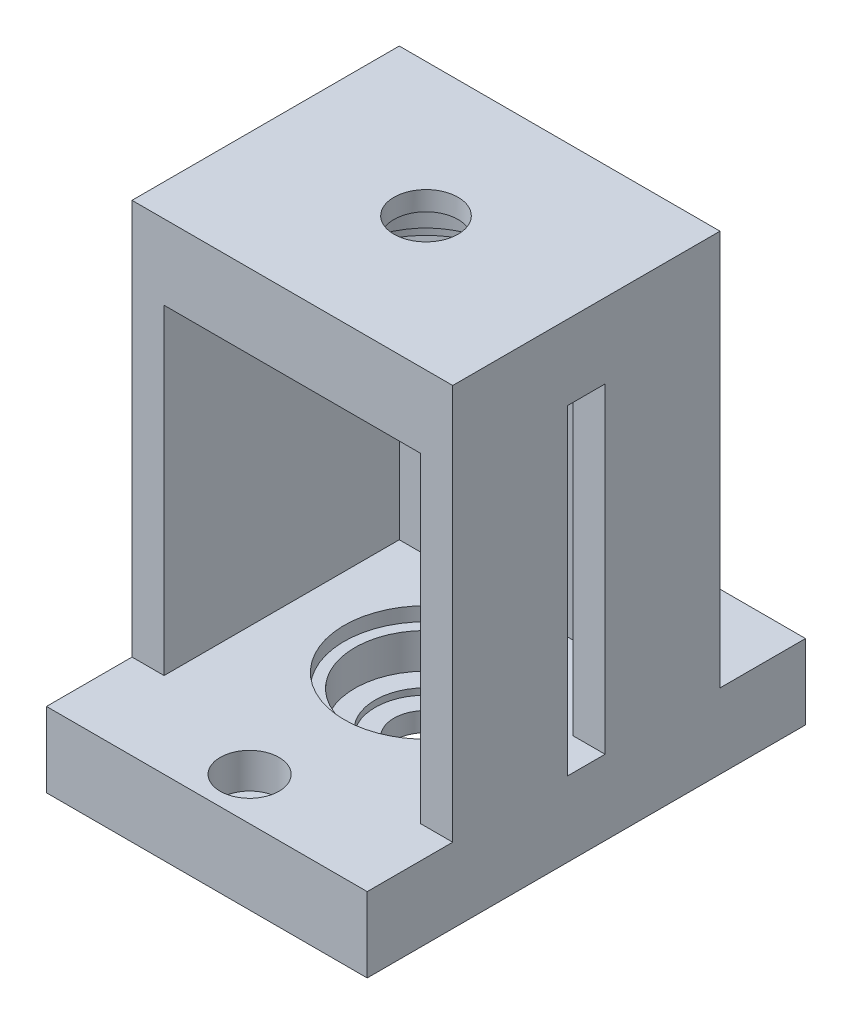
SolidWorks part; units mm, degrees
ref_plane "Front Plane" through (0, 0, 0) normal (0, 0, 1) x (1, 0, 0)
ref_plane "Top Plane" through (0, 0, 0) normal (0, 1, 0) x (1, 0, 0)
ref_plane "Right Plane" through (0, 0, 0) normal (1, 0, 0) x (0, 0, -1)
sketch "Sketch1" plane through (0, 0, 0) normal (0, 1, 0) x (1, 0, 0)
  line L1 (-15, -12.5) -> (15, -12.5)
  line L2 (-15, -12.5) -> (-15, 12.5)
  line L3 (-15, 12.5) -> (15, 12.5)
  line L4 (15, -12.5) -> (15, 12.5)
  line L5 (-15, -12.5) -> (15, 12.5) construction
  line L6 (-15, 12.5) -> (15, -12.5) construction
  point P0 (0, 0)
  dimension "D1" = 30
  dimension "D2" = 25
extrude "Boss-Extrude1" add sketch "Sketch1" along normal blind 7
sketch "Sketch2" plane through (0, 7, 0) normal (0, 1, 0) x (1, 0, 0)
  line L0 (-15, -12.5) -> (-12, -12.5)
  line L1 (-15, -12.5) -> (15, -12.5) construction
  line L2 (-12, -12.5) -> (-12, 9.5)
  line L3 (-12, 9.5) -> (12, 9.5)
  line L4 (15, -12.5) -> (15, 12.5)
  line L5 (15, 12.5) -> (-15, 12.5)
  line L6 (-15, 12.5) -> (-15, -12.5)
  line L7 (-15, -12.5) -> (15, -12.5)
  line L8 (15, -12.5) -> (15, 12.5)
  line L9 (15, 12.5) -> (-15, 12.5)
  line L10 (-15, 12.5) -> (-15, -12.5)
  line L12 (12, 9.5) -> (12, -12.5)
  line L13 (12, -12.5) -> (15, -12.5)
  dimension "D2" = 3
  dimension "D3" = 3
  dimension "D4" = 3
  dimension "D1" = 0
extrude "Boss-Extrude2" add sketch "Sketch2" along normal blind 30
sketch "Sketch3" plane through (0, 37, 0) normal (0, 1, 0) x (1, 0, 0)
  line L4 (15, -12.5) -> (15, 12.5)
  line L5 (-15, -12.5) -> (15, -12.5)
  line L6 (-15, 12.5) -> (-15, -12.5)
  line L7 (15, 12.5) -> (-15, 12.5)
  line L8 (15, -12.5) -> (15, 12.5)
  line L9 (-15, -12.5) -> (15, -12.5)
  line L10 (-15, 12.5) -> (-15, -12.5)
  line L11 (15, 12.5) -> (-15, 12.5)
  dimension "D1" = 0
extrude "Boss-Extrude3" add sketch "Sketch3" along normal blind 7
sketch "Sketch4" plane through (0, 7, 0) normal (0, 1, 0) x (1, 0, 0)
  circle A0 centre (0, 0) radius 7.65
  dimension "D1" = 15.3
extrude "Cut-Extrude1" cut sketch "Sketch4" against normal blind 1.3
sketch "Sketch5" plane through (0, 37, 0) normal (0, -1, 0) x (1, 0, 0)
  circle A0 centre (0, 0) radius 7.65
  dimension "D1" = 15.3
extrude "Cut-Extrude2" cut sketch "Sketch5" against normal blind 1.3
sketch "Sketch6" plane through (0, 5.7, 0) normal (0, 1, 0) x (1, 0, 0)
  circle A0 centre (0, 0) radius 6.65
  dimension "D1" = 13.3
extrude "Cut-Extrude3" cut sketch "Sketch6" against normal blind 3.3
sketch "Sketch7" plane through (0, 38.3, 0) normal (0, -1, 0) x (1, 0, 0)
  circle A0 centre (0, 0) radius 6.65
  dimension "D1" = 13.3
extrude "Cut-Extrude4" cut sketch "Sketch7" against normal blind 3.3
sketch "Sketch8" plane through (0, 2.4, 0) normal (0, 1, 0) x (1, 0, 0)
  circle A0 centre (0, 0) radius 4.75
  dimension "D1" = 9.5
extrude "Cut-Extrude5" cut sketch "Sketch8" against normal blind 0.6
sketch "Sketch9" plane through (0, 41.6, 0) normal (0, -1, 0) x (1, 0, 0)
  circle A0 centre (0, 0) radius 4.75
  dimension "D1" = 9.5
extrude "Cut-Extrude6" cut sketch "Sketch9" against normal blind 0.6
sketch "Sketch10" plane through (0, 1.8, 0) normal (0, 1, 0) x (1, 0, 0)
  circle A0 centre (0, 0) radius 3
  dimension "D1" = 6
extrude "Cut-Extrude7" cut sketch "Sketch10" against normal through all both and the other way through all
sketch "Sketch11" plane through (15, 0, 0) normal (1, 0, 0) x (0, 0, -1)
  line L0 (0, 44) -> (0, 0) construction
  line L1 (-12.5, 44) -> (12.5, 44) construction
  line L3 (-1.75, 7) -> (1.75, 7)
  line L4 (-1.75, 7) -> (-1.75, 37)
  line L5 (-1.75, 37) -> (1.75, 37)
  line L6 (1.75, 7) -> (1.75, 37)
  line L7 (-1.75, 7) -> (1.75, 37) construction
  line L8 (-1.75, 37) -> (1.75, 7) construction
  point P5 (0, 22)
  dimension "D1" = 3.5
extrude "Cut-Extrude8" cut sketch "Sketch11" against normal blind 10.6 and the other way through all
sketch "Sketch12" plane through (0, 0, 0) normal (0, 1, 0) x (1, 0, 0)
  line L0 (-15.7482, 0) -> (16.8329, 0) construction
  line L1 (-15, -12.5) -> (-15, -20.5)
  line L2 (-15, -20.5) -> (15, -20.5)
  line L3 (15, -20.5) -> (15, -12.5)
  line L4 (-15, -12.5) -> (15, -12.5)
  line L5 (-15, 12.5) -> (-15, 20.5)
  line L6 (-15, 20.5) -> (15, 20.5)
  line L7 (15, 20.5) -> (15, 12.5)
  line L8 (-15, 12.5) -> (15, 12.5)
  circle A0 centre (0, -16.5) radius 1.65
  circle A1 centre (0, 16.5) radius 1.65
  point P13 (-15, -16.5)
  dimension "D2" = 3.3
  dimension "D1" = 8
extrude "Boss-Extrude4" add sketch "Sketch12" along normal blind 7
sketch "Sketch13" plane through (0, 7, 0) normal (0, 1, 0) x (1, 0, 0)
  circle A0 centre (0, 16.5) radius 2.75
  circle A1 centre (0, -16.5) radius 2.75
  dimension "D1" = 5.5
extrude "Cut-Extrude9" cut sketch "Sketch13" against normal blind 3.3
